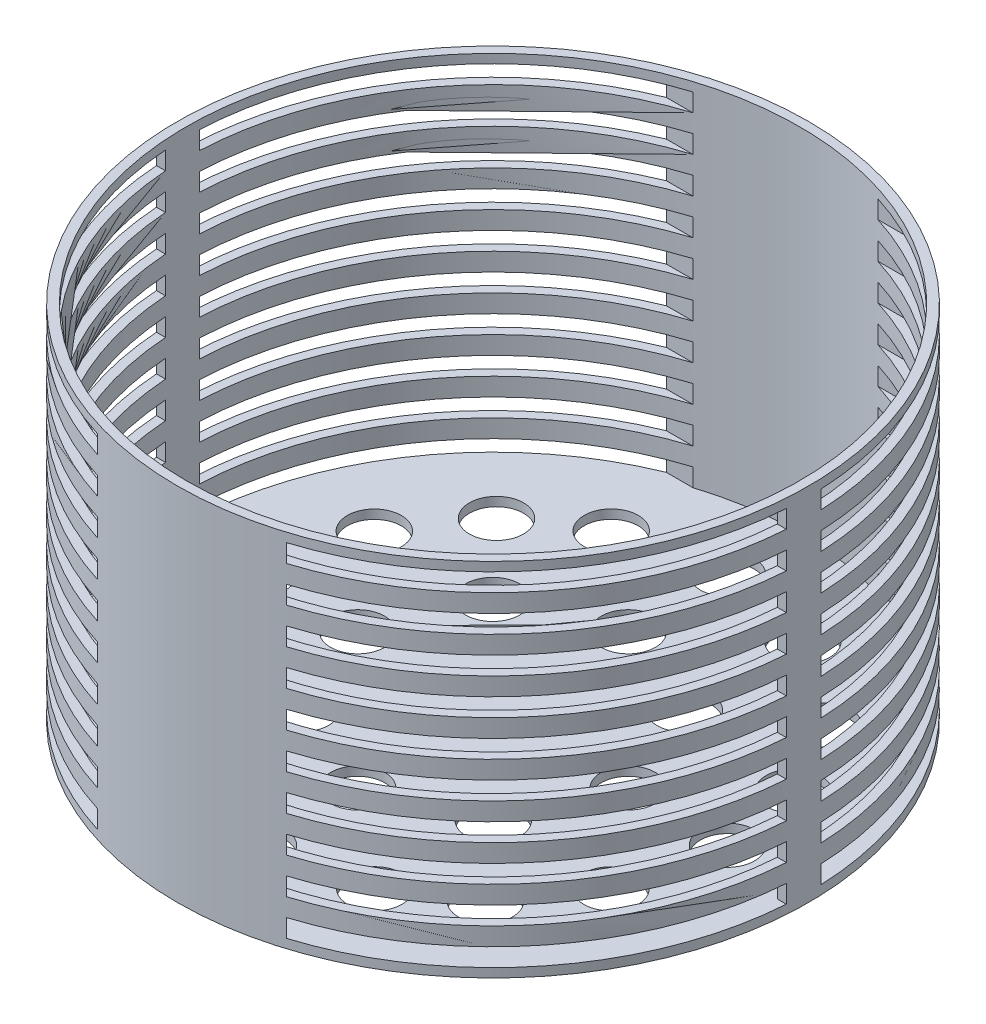
SolidWorks part; units mm, degrees
material "Plain Carbon Steel"
ref_plane "Front Plane" through (0, 0, 0) normal (0, 0, 1) x (1, 0, 0)
ref_plane "Top Plane" through (0, 0, 0) normal (0, 1, 0) x (1, 0, 0)
ref_plane "Right Plane" through (0, 0, 0) normal (1, 0, 0) x (0, 0, -1)
sketch "Sketch1" plane through (0, 0, 0) normal (0, 0, 1) x (1, 0, 0)
  line L0 (0, 0) -> (175, 0)
  line L1 (175, 0) -> (175, 200)
  line L2 (175, 200) -> (170, 200)
  line L3 (170, 200) -> (170, 5)
  line L4 (170, 5) -> (0, 5)
  line L5 (0, 5) -> (0, 0)
  dimension "D1" = 5
  dimension "D2" = 5
  dimension "D3" = 175
  dimension "D4" = 200
revolve "Revolve1" add sketch "Sketch1" angle 360 about L5
sketch "Sketch2" plane through (0, 5, 0) normal (0, 1, 0) x (1, 0, 0)
  circle A0 centre (0, 0) radius 130
  circle A1 centre (0, 0) radius 75
  circle A2 centre (0, 130) radius 15
  circle A3 centre (130, 0) radius 15
  circle A4 centre (0, -130) radius 15
  circle A5 centre (-130, 0) radius 15
  circle A6 centre (-75, 0) radius 15
  circle A7 centre (0, -75) radius 15
  circle A8 centre (0, 75) radius 15
  circle A9 centre (75, 0) radius 15
  circle A10 centre (53.1185, 52.9474) radius 15
  circle A11 centre (-53.1185, 52.9474) radius 15
  circle A12 centre (-53.1185, -52.9474) radius 15
  circle A13 centre (53.1185, -52.9474) radius 15
  circle A14 centre (53.1185, 118.6525) radius 15
  circle A15 centre (98.936, 84.3308) radius 15
  circle A16 centre (89.812, -93.9883) radius 15
  circle A17 centre (53.1185, -118.6525) radius 15
  circle A18 centre (-53.1185, 118.6525) radius 15
  circle A19 centre (-118.729, 52.9474) radius 15
  circle A20 centre (-120.9647, -47.6187) radius 15
  circle A21 centre (-97.3561, -86.1498) radius 15
  circle A22 centre (-90.9492, 92.8884) radius 15
  circle A23 centre (122.2153, 44.3105) radius 15
  circle A24 centre (118.6054, -53.2236) radius 15
  circle A25 centre (-51.6395, -119.4911) radius 15
extrude "Cut-Extrude1" cut sketch "Sketch2" against normal blind 10 contours A15 | A14 | A2 | A18 | A22 | A23 | A3 | A24 | A16 | A17 | A4 | A25 | A21 | A20 | A5 | A19 | A11 | A6 | A12 | A7 | A13 | A9 | A10 | A8
sketch "Sketch3" plane through (0, 0, 0) normal (1, 0, 0) x (0, 0, -1)
  line L0 (-166.9731, 35) -> (-11.9731, 35)
  line L1 (-166.9731, 15) -> (-11.9731, 15)
  line L2 (-166.9731, 15) -> (-166.9731, 5)
  line L3 (-166.9731, 5) -> (-11.9731, 5)
  line L4 (-11.9731, 15) -> (-11.9731, 5)
  line L5 (-166.9731, 35) -> (-166.9731, 25)
  line L6 (-166.9731, 25) -> (-11.9731, 25)
  line L7 (-11.9731, 35) -> (-11.9731, 25)
  line L8 (-166.9731, 55) -> (-11.9731, 55)
  line L9 (-166.9731, 55) -> (-166.9731, 45)
  line L10 (-166.9731, 45) -> (-11.9731, 45)
  line L11 (-11.9731, 55) -> (-11.9731, 45)
  line L12 (-166.9731, 75) -> (-11.9731, 75)
  line L13 (-166.9731, 75) -> (-166.9731, 65)
  line L14 (-166.9731, 65) -> (-11.9731, 65)
  line L15 (-11.9731, 75) -> (-11.9731, 65)
  line L16 (-166.9731, 95) -> (-11.9731, 95)
  line L17 (-166.9731, 95) -> (-166.9731, 85)
  line L18 (-166.9731, 85) -> (-11.9731, 85)
  line L19 (-11.9731, 95) -> (-11.9731, 85)
  line L20 (-166.9731, 115) -> (-11.9731, 115)
  line L21 (-166.9731, 115) -> (-166.9731, 105)
  line L22 (-166.9731, 105) -> (-11.9731, 105)
  line L23 (-11.9731, 115) -> (-11.9731, 105)
  line L24 (-166.9731, 135) -> (-11.9731, 135)
  line L25 (-166.9731, 135) -> (-166.9731, 125)
  line L26 (-166.9731, 125) -> (-11.9731, 125)
  line L27 (-11.9731, 135) -> (-11.9731, 125)
  line L28 (-166.9731, 155) -> (-11.9731, 155)
  line L29 (-166.9731, 155) -> (-166.9731, 145)
  line L30 (-166.9731, 145) -> (-11.9731, 145)
  line L31 (-11.9731, 155) -> (-11.9731, 145)
  line L32 (-166.9731, 175) -> (-11.9731, 175)
  line L33 (-166.9731, 175) -> (-166.9731, 165)
  line L34 (-166.9731, 165) -> (-11.9731, 165)
  line L35 (-11.9731, 175) -> (-11.9731, 165)
  line L36 (-166.9731, 195) -> (-11.9731, 195)
  line L37 (-166.9731, 195) -> (-166.9731, 185)
  line L38 (-166.9731, 185) -> (-11.9731, 185)
  line L39 (-11.9731, 195) -> (-11.9731, 185)
  line L40 (-175, 0) -> (175, 0) construction
  line L41 (7.0802, 35) -> (162.0802, 35)
  line L42 (7.0802, 15) -> (162.0802, 15)
  line L43 (7.0802, 15) -> (7.0802, 5)
  line L44 (7.0802, 5) -> (162.0802, 5)
  line L45 (162.0802, 15) -> (162.0802, 5)
  line L46 (7.0802, 35) -> (7.0802, 25)
  line L47 (7.0802, 25) -> (162.0802, 25)
  line L48 (162.0802, 35) -> (162.0802, 25)
  line L49 (7.0802, 55) -> (162.0802, 55)
  line L50 (7.0802, 55) -> (7.0802, 45)
  line L51 (7.0802, 45) -> (162.0802, 45)
  line L52 (162.0802, 55) -> (162.0802, 45)
  line L53 (7.0802, 75) -> (162.0802, 75)
  line L54 (7.0802, 75) -> (7.0802, 65)
  line L55 (7.0802, 65) -> (162.0802, 65)
  line L56 (162.0802, 75) -> (162.0802, 65)
  line L57 (7.0802, 95) -> (162.0802, 95)
  line L58 (7.0802, 95) -> (7.0802, 85)
  line L59 (7.0802, 85) -> (162.0802, 85)
  line L60 (162.0802, 95) -> (162.0802, 85)
  line L61 (7.0802, 115) -> (162.0802, 115)
  line L62 (7.0802, 115) -> (7.0802, 105)
  line L63 (7.0802, 105) -> (162.0802, 105)
  line L64 (162.0802, 115) -> (162.0802, 105)
  line L65 (7.0802, 135) -> (162.0802, 135)
  line L66 (7.0802, 135) -> (7.0802, 125)
  line L67 (7.0802, 125) -> (162.0802, 125)
  line L68 (162.0802, 135) -> (162.0802, 125)
  line L69 (7.0802, 155) -> (162.0802, 155)
  line L70 (7.0802, 155) -> (7.0802, 145)
  line L71 (7.0802, 145) -> (162.0802, 145)
  line L72 (162.0802, 155) -> (162.0802, 145)
  line L73 (7.0802, 175) -> (162.0802, 175)
  line L74 (7.0802, 175) -> (7.0802, 165)
  line L75 (7.0802, 165) -> (162.0802, 165)
  line L76 (162.0802, 175) -> (162.0802, 165)
  line L77 (7.0802, 195) -> (162.0802, 195)
  line L78 (7.0802, 195) -> (7.0802, 185)
  line L79 (7.0802, 185) -> (162.0802, 185)
  line L80 (162.0802, 195) -> (162.0802, 185)
  dimension "D1" = 10
  dimension "D2" = 155
  dimension "D3" = 155
  dimension "D4" = 155
  dimension "D5" = 155
  dimension "D6" = 155
  dimension "D7" = 155
  dimension "D8" = 155
  dimension "D9" = 155
  dimension "D10" = 155
  dimension "D11" = 155
  dimension "D12" = 5
  dimension "D13" = 10
  dimension "D14" = 10
  dimension "D15" = 10
  dimension "D16" = 10
  dimension "D17" = 10
  dimension "D18" = 10
  dimension "D19" = 10
  dimension "D20" = 10
  dimension "D21" = 10
  dimension "D22" = 10
  dimension "D23" = 155
  dimension "D24" = 155
  dimension "D25" = 155
  dimension "D26" = 155
  dimension "D27" = 155
  dimension "D28" = 155
  dimension "D29" = 155
  dimension "D30" = 155
  dimension "D31" = 155
  dimension "D32" = 155
  dimension "D33" = 10
  dimension "D34" = 10
  dimension "D35" = 10
  dimension "D36" = 10
  dimension "D37" = 10
  dimension "D38" = 10
  dimension "D39" = 10
  dimension "D40" = 10
  dimension "D41" = 10
extrude "Cut-Extrude2" cut sketch "Sketch3" against normal through all and the other way through all
